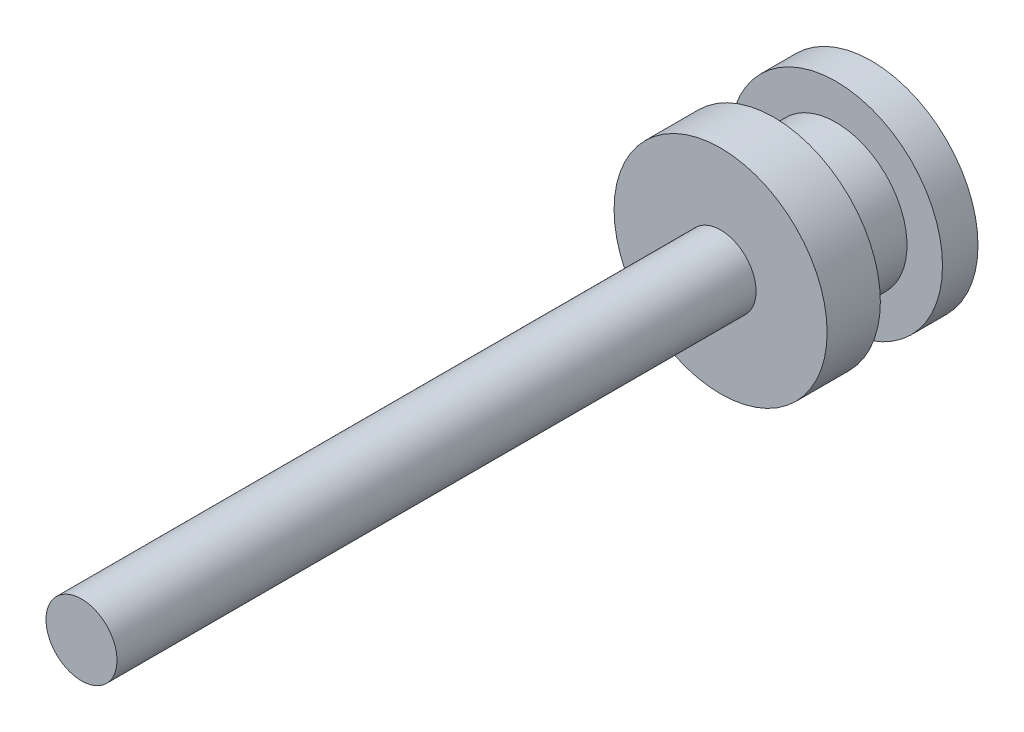
SolidWorks part; units mm, degrees
material "Titan"
ref_plane "Ebene vorne" through (0, 0, 0) normal (0, 0, 1) x (1, 0, 0)
ref_plane "Ebene oben" through (0, 0, 0) normal (0, 1, 0) x (1, 0, 0)
ref_plane "Ebene rechts" through (0, 0, 0) normal (1, 0, 0) x (0, 0, -1)
sketch "Skizze1" plane through (0, 0, 0) normal (0, 0, 1) x (1, 0, 0)
  circle A0 centre (0, 0) radius 60
  point P0 (0, 0)
  dimension "D1" = 120
extrude "Aufsatz-Linear austragen1" add sketch "Skizze1" along normal blind 30
sketch "Skizze2" plane through (0, 0, 30) normal (0, 0, 1) x (1, 0, 0)
  circle A0 centre (0, 0) radius 20
extrude "Aufsatz-Linear austragen2" add sketch "Skizze2" along normal blind 360
sketch "Skizze3" plane through (0, 0, 0) normal (0, 0, -1) x (-1, 0, 0)
  circle A0 centre (0, 0) radius 40
extrude "Aufsatz-Linear austragen3" add sketch "Skizze3" along normal blind 35
sketch "Skizze4" plane through (0, 0, -35) normal (0, 0, -1) x (-1, 0, 0)
  circle A0 centre (0, 0) radius 60
extrude "Aufsatz-Linear austragen4" add sketch "Skizze4" along normal blind 20
